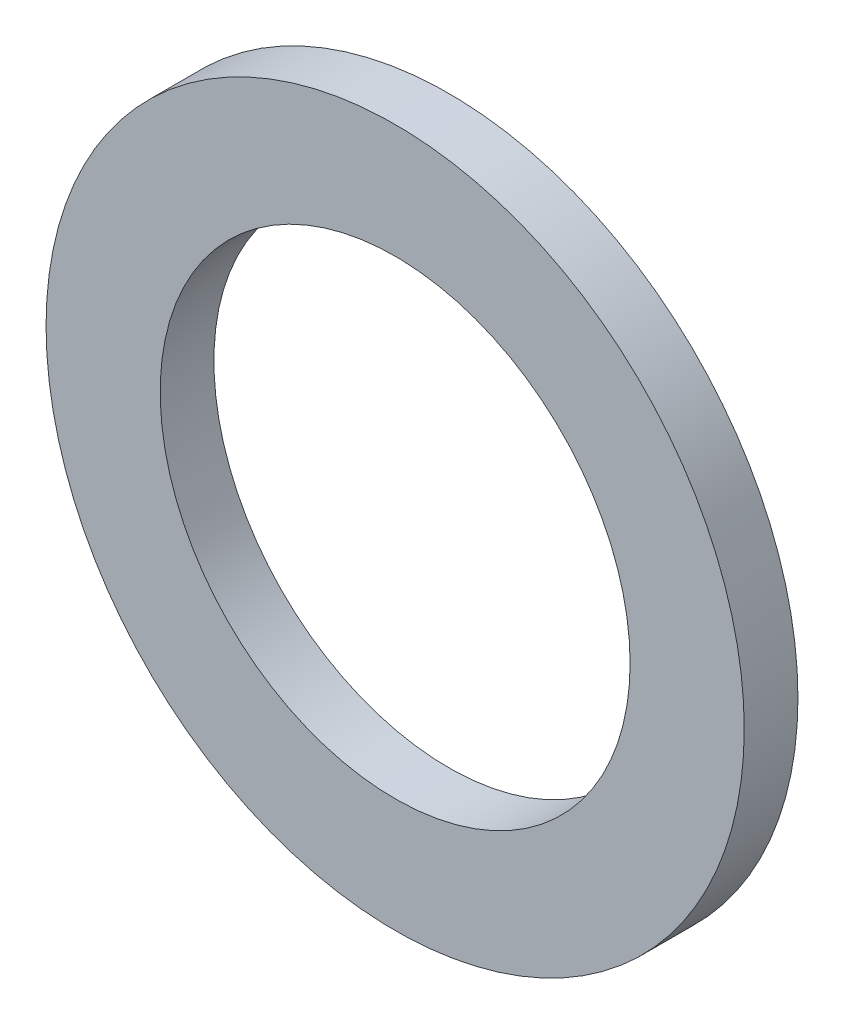
SolidWorks part; units mm, degrees
ref_plane "Front Plane" through (0, 0, 0) normal (0, 0, 1) x (1, 0, 0)
ref_plane "Top Plane" through (0, 0, 0) normal (0, 1, 0) x (1, 0, 0)
ref_plane "Right Plane" through (0, 0, 0) normal (1, 0, 0) x (0, 0, -1)
sketch "Sketch1" plane through (0, 0, 0) normal (0, 0, 1) x (1, 0, 0)
  circle A0 centre (0, 0) radius 17.5
  circle A1 centre (0, 0) radius 26
  dimension "D1" = 52
  dimension "D2" = 35
extrude "Boss-Extrude1" add sketch "Sketch1" along normal blind 4
